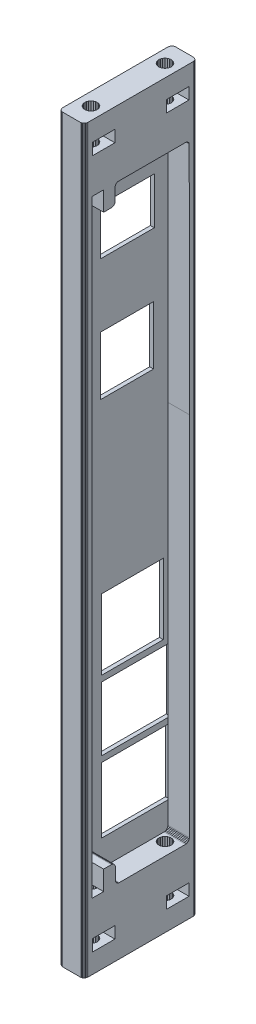
SolidWorks part; units mm, degrees
ref_plane "Front Plane" through (0, 0, 0) normal (0, 0, 1) x (1, 0, 0)
ref_plane "Top Plane" through (0, 0, 0) normal (0, 1, 0) x (1, 0, 0)
ref_plane "Right Plane" through (0, 0, 0) normal (1, 0, 0) x (0, 0, -1)
ref_plane "Plane1" through (0, 130, 0) normal (0, 1, 0) x (1, 0, 0)
sketch "Sketch1" plane through (0, 130, 0) normal (0, 1, 0) x (1, 0, 0)
  line L0 (-2.75, 35.134) -> (-2.5088, 35.0341)
  line L1 (-2.5088, 35.0341) -> (-2.25, 35)
  line L2 (-2.25, 35) -> (2.25, 35)
  line L3 (2.25, 35) -> (2.5088, 35.0341)
  line L4 (2.5088, 35.0341) -> (2.75, 35.134)
  line L5 (2.75, 35.134) -> (2.9571, 35.2929)
  line L6 (2.9571, 35.2929) -> (3.116, 35.5)
  line L7 (3.116, 35.5) -> (3.2159, 35.7412)
  line L8 (3.2159, 35.7412) -> (3.25, 36)
  line L9 (3.25, 36) -> (3.25, 63)
  line L10 (3.25, 63) -> (3.2159, 63.2588)
  line L11 (3.2159, 63.2588) -> (3.116, 63.5)
  line L12 (3.116, 63.5) -> (2.9571, 63.7071)
  line L13 (2.9571, 63.7071) -> (2.75, 63.866)
  line L14 (2.75, 63.866) -> (2.5088, 63.9659)
  line L15 (2.5088, 63.9659) -> (2.25, 64)
  line L16 (2.25, 64) -> (-2.25, 64)
  line L17 (-2.25, 64) -> (-2.5088, 63.9659)
  line L18 (-2.5088, 63.9659) -> (-2.75, 63.866)
  line L19 (-2.75, 63.866) -> (-2.9571, 63.7071)
  line L20 (-2.9571, 63.7071) -> (-3.116, 63.5)
  line L21 (-3.116, 63.5) -> (-3.2159, 63.2588)
  line L22 (-3.2159, 63.2588) -> (-3.25, 63)
  line L23 (-3.25, 63) -> (-3.25, 36)
  line L24 (-3.25, 36) -> (-3.2159, 35.7412)
  line L25 (-3.2159, 35.7412) -> (-3.116, 35.5)
  line L26 (-3.116, 35.5) -> (-2.9571, 35.2929)
  line L27 (-2.9571, 35.2929) -> (-2.75, 35.134)
extrude "Boss-Extrude1" add sketch "Sketch1" against normal blind 190
sketch "Sketch2" plane through (3.25, 0, 0) normal (1, 0, 0) x (0, 0, -1)
  line L0 (37.1, -52) -> (37.1, -55)
  line L1 (37.1, -55) -> (42.9, -55)
  line L2 (42.9, -55) -> (42.9, -52)
  line L3 (42.9, -52) -> (37.1, -52)
  line L4 (36, -60) -> (63, -60) construction
  dimension "D1" = 5
extrude "Cut-Extrude1" cut sketch "Sketch2" against normal through all
sketch "Sketch3" plane through (0, -60, 0) normal (0, -1, 0) x (1, 0, 0)
  line L0 (-1.5455, -40.4141) -> (-1.3856, -40.8)
  line L1 (-1.3856, -40.8) -> (-1.1314, -41.1314)
  line L2 (-1.1314, -41.1314) -> (-0.8, -41.3856)
  line L3 (-0.8, -41.3856) -> (-0.4141, -41.5455)
  line L4 (-0.4141, -41.5455) -> (0, -41.6)
  line L5 (0, -41.6) -> (0.4141, -41.5455)
  line L6 (0.4141, -41.5455) -> (0.8, -41.3856)
  line L7 (0.8, -41.3856) -> (1.1314, -41.1314)
  line L8 (1.1314, -41.1314) -> (1.3856, -40.8)
  line L9 (1.3856, -40.8) -> (1.5455, -40.4141)
  line L10 (1.5455, -40.4141) -> (1.6, -40)
  line L11 (1.6, -40) -> (1.5455, -39.5859)
  line L12 (1.5455, -39.5859) -> (1.3856, -39.2)
  line L13 (1.3856, -39.2) -> (1.1314, -38.8686)
  line L14 (1.1314, -38.8686) -> (0.8, -38.6144)
  line L15 (0.8, -38.6144) -> (0.4141, -38.4545)
  line L16 (0.4141, -38.4545) -> (0, -38.4)
  line L17 (0, -38.4) -> (-0.4141, -38.4545)
  line L18 (-0.4141, -38.4545) -> (-0.8, -38.6144)
  line L19 (-0.8, -38.6144) -> (-1.1314, -38.8686)
  line L20 (-1.1314, -38.8686) -> (-1.3856, -39.2)
  line L21 (-1.3856, -39.2) -> (-1.5455, -39.5859)
  line L22 (-1.5455, -39.5859) -> (-1.6, -40)
  line L23 (-1.6, -40) -> (-1.5455, -40.4141)
extrude "Cut-Extrude2" cut sketch "Sketch3" against normal up to next
sketch "Sketch4" plane through (3.25, 0, 0) normal (1, 0, 0) x (0, 0, -1)
  line L0 (37.1, 125) -> (37.1, 122)
  line L1 (37.1, 122) -> (42.9, 122)
  line L2 (42.9, 122) -> (42.9, 125)
  line L3 (42.9, 125) -> (37.1, 125)
extrude "Cut-Extrude3" cut sketch "Sketch4" against normal through all
sketch "Sketch5" plane through (3.25, 0, 0) normal (1, 0, 0) x (0, 0, -1)
  line L0 (61.9, 125) -> (56.1, 125)
  line L1 (56.1, 125) -> (56.1, 122)
  line L2 (56.1, 122) -> (61.9, 122)
  line L3 (61.9, 122) -> (61.9, 125)
extrude "Cut-Extrude4" cut sketch "Sketch5" against normal through all
sketch "Sketch6" plane through (0, 130, 0) normal (0, 1, 0) x (-1, 0, 0)
  line L0 (1.5455, -39.5859) -> (1.3856, -39.2)
  line L1 (1.3856, -39.2) -> (1.1314, -38.8686)
  line L2 (1.1314, -38.8686) -> (0.8, -38.6144)
  line L3 (0.8, -38.6144) -> (0.4141, -38.4545)
  line L4 (0.4141, -38.4545) -> (0, -38.4)
  line L5 (0, -38.4) -> (-0.4141, -38.4545)
  line L6 (-0.4141, -38.4545) -> (-0.8, -38.6144)
  line L7 (-0.8, -38.6144) -> (-1.1314, -38.8686)
  line L8 (-1.1314, -38.8686) -> (-1.3856, -39.2)
  line L9 (-1.3856, -39.2) -> (-1.5455, -39.5859)
  line L10 (-1.5455, -39.5859) -> (-1.6, -40)
  line L11 (-1.6, -40) -> (-1.5455, -40.4141)
  line L12 (-1.5455, -40.4141) -> (-1.3856, -40.8)
  line L13 (-1.3856, -40.8) -> (-1.1314, -41.1314)
  line L14 (-1.1314, -41.1314) -> (-0.8, -41.3856)
  line L15 (-0.8, -41.3856) -> (-0.4141, -41.5455)
  line L16 (-0.4141, -41.5455) -> (0, -41.6)
  line L17 (0, -41.6) -> (0.4141, -41.5455)
  line L18 (0.4141, -41.5455) -> (0.8, -41.3856)
  line L19 (0.8, -41.3856) -> (1.1314, -41.1314)
  line L20 (1.1314, -41.1314) -> (1.3856, -40.8)
  line L21 (1.3856, -40.8) -> (1.5455, -40.4141)
  line L22 (1.5455, -40.4141) -> (1.6, -40)
  line L23 (1.6, -40) -> (1.5455, -39.5859)
extrude "Cut-Extrude5" cut sketch "Sketch6" against normal up to next
sketch "Sketch7" plane through (0, 130, 0) normal (0, 1, 0) x (-1, 0, 0)
  line L0 (-1.6, -59) -> (-1.5455, -59.4141)
  line L1 (-1.5455, -59.4141) -> (-1.3856, -59.8)
  line L2 (-1.3856, -59.8) -> (-1.1314, -60.1314)
  line L3 (-1.1314, -60.1314) -> (-0.8, -60.3856)
  line L4 (-0.8, -60.3856) -> (-0.4141, -60.5455)
  line L5 (-0.4141, -60.5455) -> (0, -60.6)
  line L6 (0, -60.6) -> (0.4141, -60.5455)
  line L7 (0.4141, -60.5455) -> (0.8, -60.3856)
  line L8 (0.8, -60.3856) -> (1.1314, -60.1314)
  line L9 (1.1314, -60.1314) -> (1.3856, -59.8)
  line L10 (1.3856, -59.8) -> (1.5455, -59.4141)
  line L11 (1.5455, -59.4141) -> (1.6, -59)
  line L12 (1.6, -59) -> (1.5455, -58.5859)
  line L13 (1.5455, -58.5859) -> (1.3856, -58.2)
  line L14 (1.3856, -58.2) -> (1.1314, -57.8686)
  line L15 (1.1314, -57.8686) -> (0.8, -57.6144)
  line L16 (0.8, -57.6144) -> (0.4141, -57.4545)
  line L17 (0.4141, -57.4545) -> (0, -57.4)
  line L18 (0, -57.4) -> (-0.4141, -57.4545)
  line L19 (-0.4141, -57.4545) -> (-0.8, -57.6144)
  line L20 (-0.8, -57.6144) -> (-1.1314, -57.8686)
  line L21 (-1.1314, -57.8686) -> (-1.3856, -58.2)
  line L22 (-1.3856, -58.2) -> (-1.5455, -58.5859)
  line L23 (-1.5455, -58.5859) -> (-1.6, -59)
extrude "Cut-Extrude6" cut sketch "Sketch7" against normal up to next
sketch "Sketch8" plane through (3.25, 0, 0) normal (1, 0, 0) x (0, 0, -1)
  line L0 (56.1, -52) -> (56.1, -55)
  line L1 (56.1, -55) -> (61.9, -55)
  line L2 (61.9, -55) -> (61.9, -52)
  line L3 (61.9, -52) -> (56.1, -52)
  line L4 (36, -60) -> (63, -60) construction
  dimension "D1" = 5
extrude "Cut-Extrude7" cut sketch "Sketch8" against normal through all
sketch "Sketch9" plane through (0, -60, 0) normal (0, -1, 0) x (1, 0, 0)
  line L0 (-0.8, -57.6144) -> (-1.1314, -57.8686)
  line L1 (-1.1314, -57.8686) -> (-1.3856, -58.2)
  line L2 (-1.3856, -58.2) -> (-1.5455, -58.5859)
  line L3 (-1.5455, -58.5859) -> (-1.6, -59)
  line L4 (-1.6, -59) -> (-1.5455, -59.4141)
  line L5 (-1.5455, -59.4141) -> (-1.3856, -59.8)
  line L6 (-1.3856, -59.8) -> (-1.1314, -60.1314)
  line L7 (-1.1314, -60.1314) -> (-0.8, -60.3856)
  line L8 (-0.8, -60.3856) -> (-0.4141, -60.5455)
  line L9 (-0.4141, -60.5455) -> (0, -60.6)
  line L10 (0, -60.6) -> (0.4141, -60.5455)
  line L11 (0.4141, -60.5455) -> (0.8, -60.3856)
  line L12 (0.8, -60.3856) -> (1.1314, -60.1314)
  line L13 (1.1314, -60.1314) -> (1.3856, -59.8)
  line L14 (1.3856, -59.8) -> (1.5455, -59.4141)
  line L15 (1.5455, -59.4141) -> (1.6, -59)
  line L16 (1.6, -59) -> (1.5455, -58.5859)
  line L17 (1.5455, -58.5859) -> (1.3856, -58.2)
  line L18 (1.3856, -58.2) -> (1.1314, -57.8686)
  line L19 (1.1314, -57.8686) -> (0.8, -57.6144)
  line L20 (0.8, -57.6144) -> (0.4141, -57.4545)
  line L21 (0.4141, -57.4545) -> (0, -57.4)
  line L22 (0, -57.4) -> (-0.4141, -57.4545)
  line L23 (-0.4141, -57.4545) -> (-0.8, -57.6144)
extrude "Cut-Extrude8" cut sketch "Sketch9" against normal up to next
sketch "Sketch10" plane through (3.25, 0, 0) normal (1, 0, 0) x (0, 0, -1)
  line L0 (62, -42) -> (62, 52)
  line L1 (62, 52) -> (61.9659, 112.2588)
  line L2 (61.9659, 112.2588) -> (61.866, 112.5)
  line L3 (61.866, 112.5) -> (61.7071, 112.7071)
  line L4 (61.7071, 112.7071) -> (61.5, 112.866)
  line L5 (61.5, 112.866) -> (61.2588, 112.9659)
  line L6 (61.2588, 112.9659) -> (61, 113)
  line L7 (61, 113) -> (44, 113)
  line L8 (42.9659, 108.7412) -> (42.9659, 112.2588)
  line L9 (36, -60) -> (63, -60) construction
  line L16 (42.9659, 108.7412) -> (42.866, 108.5)
  line L17 (42.866, 108.5) -> (42.7071, 108.2929)
  line L18 (42.7071, 108.2929) -> (42.5, 108.134)
  line L19 (42.5, 108.134) -> (42.2588, 108.0341)
  line L20 (42.2588, 108.0341) -> (42, 108)
  line L21 (42, 108) -> (40, 108)
  line L22 (40, 108) -> (40, 113)
  line L23 (40, 113) -> (37, 113)
  line L24 (37, 113) -> (37, -43)
  line L25 (37, -43) -> (40, -43)
  line L26 (40, -43) -> (40, -38)
  line L27 (40, -38) -> (42, -38)
  line L28 (42, -38) -> (42.2588, -38.0341)
  line L29 (42.2588, -38.0341) -> (42.5, -38.134)
  line L30 (42.5, -38.134) -> (42.7071, -38.2929)
  line L31 (42.7071, -38.2929) -> (42.866, -38.5)
  line L32 (42.866, -38.5) -> (42.9659, -38.7412)
  line L33 (42.9659, -38.7412) -> (43, -39)
  line L34 (43, -39) -> (43, -42)
  line L35 (43, -42) -> (43.0341, -42.2588)
  line L36 (43.0341, -42.2588) -> (43.134, -42.5)
  line L37 (43.134, -42.5) -> (43.2929, -42.7071)
  line L38 (43.2929, -42.7071) -> (43.5, -42.866)
  line L39 (43.5, -42.866) -> (43.7412, -42.9659)
  line L40 (43.7412, -42.9659) -> (44, -43)
  line L41 (44, -43) -> (61, -43)
  line L42 (61, -43) -> (61.2588, -42.9659)
  line L43 (61.2588, -42.9659) -> (61.5, -42.866)
  line L44 (61.5, -42.866) -> (61.7071, -42.7071)
  line L45 (61.7071, -42.7071) -> (61.866, -42.5)
  line L46 (61.866, -42.5) -> (61.9659, -42.2588)
  line L47 (61.9659, -42.2588) -> (62, -42)
  line L48 (36, 130) -> (63, 130) construction
  line L49 (62, 35) -> (37, 35) construction
  arc A0 (42.9659, 112.2588) -> (44, 113) centre (43.8536, 112.1124) cw
  dimension "D1" = 156
  dimension "D2" = 17
  dimension "D3" = 5
  dimension "D4" = 5
  dimension "D5" = 78
  dimension "D6" = 17
extrude "Cut-Extrude9" cut sketch "Sketch10" against normal blind 5.5
sketch "Sketch11" plane through (0, 122, 0) normal (0, 1, 0) x (-1, 0, 0)
  line L0 (1.5455, -40.4141) -> (1.6, -40)
  line L1 (1.6, -40) -> (1.5455, -39.5859)
  line L2 (1.5455, -39.5859) -> (1.3856, -39.2)
  line L3 (1.3856, -39.2) -> (1.1314, -38.8686)
  line L4 (1.1314, -38.8686) -> (0.8, -38.6144)
  line L5 (0.8, -38.6144) -> (0.4141, -38.4545)
  line L6 (0.4141, -38.4545) -> (0, -38.4)
  line L7 (0, -38.4) -> (-0.4141, -38.4545)
  line L8 (-0.4141, -38.4545) -> (-0.8, -38.6144)
  line L9 (-0.8, -38.6144) -> (-1.1314, -38.8686)
  line L10 (-1.1314, -38.8686) -> (-1.3856, -39.2)
  line L11 (-1.3856, -39.2) -> (-1.5455, -39.5859)
  line L12 (-1.5455, -39.5859) -> (-1.6, -40)
  line L13 (-1.6, -40) -> (-1.5455, -40.4141)
  line L14 (-1.5455, -40.4141) -> (-1.3856, -40.8)
  line L15 (-1.3856, -40.8) -> (-1.1314, -41.1314)
  line L16 (-1.1314, -41.1314) -> (-0.8, -41.3856)
  line L17 (-0.8, -41.3856) -> (-0.4141, -41.5455)
  line L18 (-0.4141, -41.5455) -> (0, -41.6)
  line L19 (0, -41.6) -> (0.4141, -41.5455)
  line L20 (0.4141, -41.5455) -> (0.8, -41.3856)
  line L21 (0.8, -41.3856) -> (1.1314, -41.1314)
  line L22 (1.1314, -41.1314) -> (1.3856, -40.8)
  line L23 (1.3856, -40.8) -> (1.5455, -40.4141)
extrude "Cut-Extrude10" cut sketch "Sketch11" against normal up to surface (9 mm away) up to face at (0.5, 113, -38.5)
sketch "Sketch12" plane through (0, 122, 0) normal (0, 1, 0) x (-1, 0, 0)
  line L0 (1.5455, -59.4141) -> (1.6, -59)
  line L1 (1.6, -59) -> (1.5455, -58.5859)
  line L2 (1.5455, -58.5859) -> (1.3856, -58.2)
  line L3 (1.3856, -58.2) -> (1.1314, -57.8686)
  line L4 (1.1314, -57.8686) -> (0.8, -57.6144)
  line L5 (0.8, -57.6144) -> (0.4141, -57.4545)
  line L6 (0.4141, -57.4545) -> (0, -57.4)
  line L7 (0, -57.4) -> (-0.4141, -57.4545)
  line L8 (-0.4141, -57.4545) -> (-0.8, -57.6144)
  line L9 (-0.8, -57.6144) -> (-1.1314, -57.8686)
  line L10 (-1.1314, -57.8686) -> (-1.3856, -58.2)
  line L11 (-1.3856, -58.2) -> (-1.5455, -58.5859)
  line L12 (-1.5455, -58.5859) -> (-1.6, -59)
  line L13 (-1.6, -59) -> (-1.5455, -59.4141)
  line L14 (-1.5455, -59.4141) -> (-1.3856, -59.8)
  line L15 (-1.3856, -59.8) -> (-1.1314, -60.1314)
  line L16 (-1.1314, -60.1314) -> (-0.8, -60.3856)
  line L17 (-0.8, -60.3856) -> (-0.4141, -60.5455)
  line L18 (-0.4141, -60.5455) -> (0, -60.6)
  line L19 (0, -60.6) -> (0.4141, -60.5455)
  line L20 (0.4141, -60.5455) -> (0.8, -60.3856)
  line L21 (0.8, -60.3856) -> (1.1314, -60.1314)
  line L22 (1.1314, -60.1314) -> (1.3856, -59.8)
  line L23 (1.3856, -59.8) -> (1.5455, -59.4141)
extrude "Cut-Extrude11" cut sketch "Sketch12" against normal up to surface (9 mm away) up to face at (0.5, 113, -52.5)
sketch "Sketch13" plane through (0, -52, 0) normal (0, -1, 0) x (1, 0, 0)
  line L0 (-0.4141, -41.5455) -> (0, -41.6)
  line L1 (0, -41.6) -> (0.4141, -41.5455)
  line L2 (0.4141, -41.5455) -> (0.8, -41.3856)
  line L3 (0.8, -41.3856) -> (1.1314, -41.1314)
  line L4 (1.1314, -41.1314) -> (1.3856, -40.8)
  line L5 (1.3856, -40.8) -> (1.5455, -40.4141)
  line L6 (1.5455, -40.4141) -> (1.6, -40)
  line L7 (1.6, -40) -> (1.5455, -39.5859)
  line L8 (1.5455, -39.5859) -> (1.3856, -39.2)
  line L9 (1.3856, -39.2) -> (1.1314, -38.8686)
  line L10 (1.1314, -38.8686) -> (0.8, -38.6144)
  line L11 (0.8, -38.6144) -> (0.4141, -38.4545)
  line L12 (0.4141, -38.4545) -> (0, -38.4)
  line L13 (0, -38.4) -> (-0.4141, -38.4545)
  line L14 (-0.4141, -38.4545) -> (-0.8, -38.6144)
  line L15 (-0.8, -38.6144) -> (-1.1314, -38.8686)
  line L16 (-1.1314, -38.8686) -> (-1.3856, -39.2)
  line L17 (-1.3856, -39.2) -> (-1.5455, -39.5859)
  line L18 (-1.5455, -39.5859) -> (-1.6, -40)
  line L19 (-1.6, -40) -> (-1.5455, -40.4141)
  line L20 (-1.5455, -40.4141) -> (-1.3856, -40.8)
  line L21 (-1.3856, -40.8) -> (-1.1314, -41.1314)
  line L22 (-1.1314, -41.1314) -> (-0.8, -41.3856)
  line L23 (-0.8, -41.3856) -> (-0.4141, -41.5455)
extrude "Cut-Extrude12" cut sketch "Sketch13" against normal up to surface (9 mm away) up to face at (0.5, -43, -38.5)
sketch "Sketch14" plane through (0, -52, 0) normal (0, -1, 0) x (1, 0, 0)
  line L0 (-0.4141, -60.5455) -> (0, -60.6)
  line L1 (0, -60.6) -> (0.4141, -60.5455)
  line L2 (0.4141, -60.5455) -> (0.8, -60.3856)
  line L3 (0.8, -60.3856) -> (1.1314, -60.1314)
  line L4 (1.1314, -60.1314) -> (1.3856, -59.8)
  line L5 (1.3856, -59.8) -> (1.5455, -59.4141)
  line L6 (1.5455, -59.4141) -> (1.6, -59)
  line L7 (1.6, -59) -> (1.5455, -58.5859)
  line L8 (1.5455, -58.5859) -> (1.3856, -58.2)
  line L9 (1.3856, -58.2) -> (1.1314, -57.8686)
  line L10 (1.1314, -57.8686) -> (0.8, -57.6144)
  line L11 (0.8, -57.6144) -> (0.4141, -57.4545)
  line L12 (0.4141, -57.4545) -> (0, -57.4)
  line L13 (0, -57.4) -> (-0.4141, -57.4545)
  line L14 (-0.4141, -57.4545) -> (-0.8, -57.6144)
  line L15 (-0.8, -57.6144) -> (-1.1314, -57.8686)
  line L16 (-1.1314, -57.8686) -> (-1.3856, -58.2)
  line L17 (-1.3856, -58.2) -> (-1.5455, -58.5859)
  line L18 (-1.5455, -58.5859) -> (-1.6, -59)
  line L19 (-1.6, -59) -> (-1.5455, -59.4141)
  line L20 (-1.5455, -59.4141) -> (-1.3856, -59.8)
  line L21 (-1.3856, -59.8) -> (-1.1314, -60.1314)
  line L22 (-1.1314, -60.1314) -> (-0.8, -60.3856)
  line L23 (-0.8, -60.3856) -> (-0.4141, -60.5455)
extrude "Cut-Extrude13" cut sketch "Sketch14" against normal up to surface (9 mm away) up to face at (0.5, -43, -52.5)
sketch "Sketch15" plane through (-2.25, 0, 0) normal (1, 0, 0) x (0, 0, -1)
  line L0 (57, 98.55) -> (46.2, 98.55) construction
  line L5 (46.2, 74.75) -> (56.8, 74.75) construction
  line L6 (46.2, 74.75) -> (46.2, 62.75) construction
  line L7 (46.2, 62.75) -> (56.8, 62.75) construction
  line L8 (56.8, 74.75) -> (56.8, 62.75) construction
  line L21 (46.2, 103.05) -> (57, 103.05) construction
  line L22 (46.2, 103.05) -> (46.2, 94.05) construction
  line L23 (46.2, 94.05) -> (57, 94.05) construction
  line L24 (57, 103.05) -> (57, 94.05) construction
  line L25 (51.6, 103.05) -> (51.6, 94.05) construction
  line L26 (51.5, 62.75) -> (51.5, 74.75) construction
  line L27 (46.2, 68.75) -> (56.8, 68.75) construction
  line L28 (60.8, 17.95) -> (45, 17.95)
  line L29 (59.8, 0.85) -> (46, 0.85) construction
  line L30 (59.8, 0.85) -> (59.8, 16.95) construction
  line L31 (59.8, 16.95) -> (46, 16.95) construction
  line L32 (46, 0.85) -> (46, 16.95) construction
  line L33 (59.8, 0.85) -> (46, 16.95) construction
  line L34 (59.8, 16.95) -> (46, 0.85) construction
  line L35 (61.6, -17.05) -> (46, -17.05) construction
  line L36 (61.6, -17.05) -> (61.6, -2.65) construction
  line L37 (61.6, -2.65) -> (46, -2.65) construction
  line L38 (46, -17.05) -> (46, -2.65) construction
  line L39 (61.6, -17.05) -> (46, -2.65) construction
  line L40 (61.6, -2.65) -> (46, -17.05) construction
  line L41 (61.9659, -42.2588) -> (62, -42)
  line L42 (62, -42) -> (62, 52)
  line L43 (62, 52) -> (61.9659, 112.2588)
  line L44 (61.9659, 112.2588) -> (61.866, 112.5)
  line L45 (61.866, 112.5) -> (61.7071, 112.7071)
  line L46 (61.7071, 112.7071) -> (61.5, 112.866)
  line L47 (61.5, 112.866) -> (61.2588, 112.9659)
  line L48 (61.2588, 112.9659) -> (61, 113)
  line L49 (61, 113) -> (44, 113)
  line L50 (42.9659, 112.2588) -> (42.9659, 108.7412)
  line L51 (42.9659, 108.7412) -> (42.866, 108.5)
  line L52 (42.866, 108.5) -> (42.7071, 108.2929)
  line L53 (42.7071, 108.2929) -> (42.5, 108.134)
  line L54 (42.5, 108.134) -> (42.2588, 108.0341)
  line L55 (42.2588, 108.0341) -> (42, 108)
  line L56 (42, 108) -> (40, 108)
  line L57 (40, 108) -> (40, 113)
  line L58 (40, 113) -> (37, 113)
  line L59 (37, 113) -> (37, -43)
  line L60 (37, -43) -> (40, -43)
  line L61 (40, -43) -> (40, -38)
  line L62 (40, -38) -> (42, -38)
  line L63 (42, -38) -> (42.2588, -38.0341)
  line L64 (42.2588, -38.0341) -> (42.5, -38.134)
  line L65 (42.5, -38.134) -> (42.7071, -38.2929)
  line L66 (42.7071, -38.2929) -> (42.866, -38.5)
  line L67 (42.866, -38.5) -> (42.9659, -38.7412)
  line L68 (42.9659, -38.7412) -> (43, -39)
  line L69 (43, -39) -> (43, -42)
  line L70 (43, -42) -> (43.0341, -42.2588)
  line L71 (43.0341, -42.2588) -> (43.134, -42.5)
  line L72 (43.134, -42.5) -> (43.2929, -42.7071)
  line L73 (43.2929, -42.7071) -> (43.5, -42.866)
  line L74 (43.5, -42.866) -> (43.7412, -42.9659)
  line L75 (43.7412, -42.9659) -> (44, -43)
  line L76 (44, -43) -> (61, -43)
  line L77 (61, -43) -> (61.2588, -42.9659)
  line L78 (61.2588, -42.9659) -> (61.5, -42.866)
  line L79 (61.5, -42.866) -> (61.7071, -42.7071)
  line L80 (61.7071, -42.7071) -> (61.866, -42.5)
  line L81 (61.866, -42.5) -> (61.9659, -42.2588)
  line L82 (61.9659, -42.2588) -> (62, -42)
  line L83 (62, -42) -> (62, 52)
  line L84 (62, 52) -> (61.9659, 112.2588)
  line L85 (61.9659, 112.2588) -> (61.866, 112.5)
  line L86 (61.866, 112.5) -> (61.7071, 112.7071)
  line L87 (61.7071, 112.7071) -> (61.5, 112.866)
  line L88 (61.5, 112.866) -> (61.2588, 112.9659)
  line L89 (61.2588, 112.9659) -> (61, 113)
  line L90 (61, 113) -> (44, 113)
  line L91 (42.9659, 112.2588) -> (42.9659, 108.7412)
  line L92 (42.9659, 108.7412) -> (42.866, 108.5)
  line L93 (42.866, 108.5) -> (42.7071, 108.2929)
  line L94 (42.7071, 108.2929) -> (42.5, 108.134)
  line L95 (42.5, 108.134) -> (42.2588, 108.0341)
  line L96 (42.2588, 108.0341) -> (42, 108)
  line L97 (42, 108) -> (40, 108)
  line L98 (40, 108) -> (40, 113)
  line L99 (40, 113) -> (37, 113)
  line L100 (37, 113) -> (37, -43)
  line L101 (37, -43) -> (40, -43)
  line L102 (40, -43) -> (40, -38)
  line L103 (40, -38) -> (42, -38)
  line L104 (42, -38) -> (42.2588, -38.0341)
  line L105 (42.2588, -38.0341) -> (42.5, -38.134)
  line L106 (42.5, -38.134) -> (42.7071, -38.2929)
  line L107 (42.7071, -38.2929) -> (42.866, -38.5)
  line L108 (42.866, -38.5) -> (42.9659, -38.7412)
  line L109 (42.9659, -38.7412) -> (43, -39)
  line L110 (43, -39) -> (43, -42)
  line L111 (43, -42) -> (43.0341, -42.2588)
  line L112 (43.0341, -42.2588) -> (43.134, -42.5)
  line L113 (43.134, -42.5) -> (43.2929, -42.7071)
  line L114 (43.2929, -42.7071) -> (43.5, -42.866)
  line L115 (43.5, -42.866) -> (43.7412, -42.9659)
  line L116 (43.7412, -42.9659) -> (44, -43)
  line L117 (44, -43) -> (61, -43)
  line L118 (61, -43) -> (61.2588, -42.9659)
  line L119 (61.2588, -42.9659) -> (61.5, -42.866)
  line L120 (61.5, -42.866) -> (61.7071, -42.7071)
  line L121 (61.7071, -42.7071) -> (61.866, -42.5)
  line L122 (61.866, -42.5) -> (61.9659, -42.2588)
  line L123 (61.4, -35.35) -> (46, -35.35) construction
  line L124 (61.4, -35.35) -> (61.4, -20.55) construction
  line L125 (61.4, -20.55) -> (46, -20.55) construction
  line L126 (46, -35.35) -> (46, -20.55) construction
  line L127 (61.4, -35.35) -> (46, -20.55) construction
  line L128 (61.4, -20.55) -> (46, -35.35) construction
  line L129 (45, -0.15) -> (45, 17.95)
  line L130 (60.8, -0.15) -> (45, -0.15)
  line L131 (60.8, -0.15) -> (60.8, 17.95)
  line L132 (62.6, -1.65) -> (45, -1.65)
  line L133 (45, -18.05) -> (45, -1.65)
  line L134 (62.6, -18.05) -> (45, -18.05)
  line L135 (62.6, -18.05) -> (62.6, -1.65)
  line L136 (62.4, -19.55) -> (45, -19.55)
  line L137 (45, -36.35) -> (45, -19.55)
  line L138 (62.4, -36.35) -> (45, -36.35)
  line L139 (62.4, -36.35) -> (62.4, -19.55)
  line L140 (44.7, 104.55) -> (58.5, 104.55)
  line L141 (58.5, 104.55) -> (58.5, 92.55)
  line L142 (44.7, 92.55) -> (58.5, 92.55)
  line L143 (44.7, 104.55) -> (44.7, 92.55)
  line L144 (58.3, 76.25) -> (58.3, 61.25)
  line L145 (44.7, 61.25) -> (58.3, 61.25)
  line L146 (44.7, 76.25) -> (44.7, 61.25)
  line L147 (44.7, 76.25) -> (58.3, 76.25)
  arc A1 (44, 113) -> (42.9659, 112.2588) centre (43.8536, 112.1124) ccw
  arc A2 (44, 113) -> (42.9659, 112.2588) centre (43.8536, 112.1124) ccw
  point P19 (52.9, 8.9)
  point P29 (53.8, -9.85)
  point P39 (53.7, -27.95)
  point P67 (53.8, -17.05)
  point P69 (52.9, 0.85)
  dimension "D2" = 9.95
  dimension "D3" = 19.3
  dimension "D4" = 12
  dimension "D5" = 10.6
  dimension "D6" = 9.2
  dimension "D7" = 9
  dimension "D8" = 10.8
  dimension "D9" = 9
  dimension "D10" = 7.65
  dimension "D11" = 3.5
  dimension "D12" = 3.5
  dimension "D13" = 16.1
  dimension "D14" = 14.4
  dimension "D15" = 14.8
  dimension "D16" = 13.8
  dimension "D17" = 15.6
  dimension "D18" = 15.4
  dimension "D1" = 0
  dimension "D19" = 1
  dimension "D20" = 1
  dimension "D21" = 1.5
extrude "Cut-Extrude14" cut sketch "Sketch15" against normal up to next contours L147 L146 L145 L144 | L140 L143 L142 L141 | L28 L129 L130 L131 | L134 L133 L132 L135 | L138 L137 L136 L139
